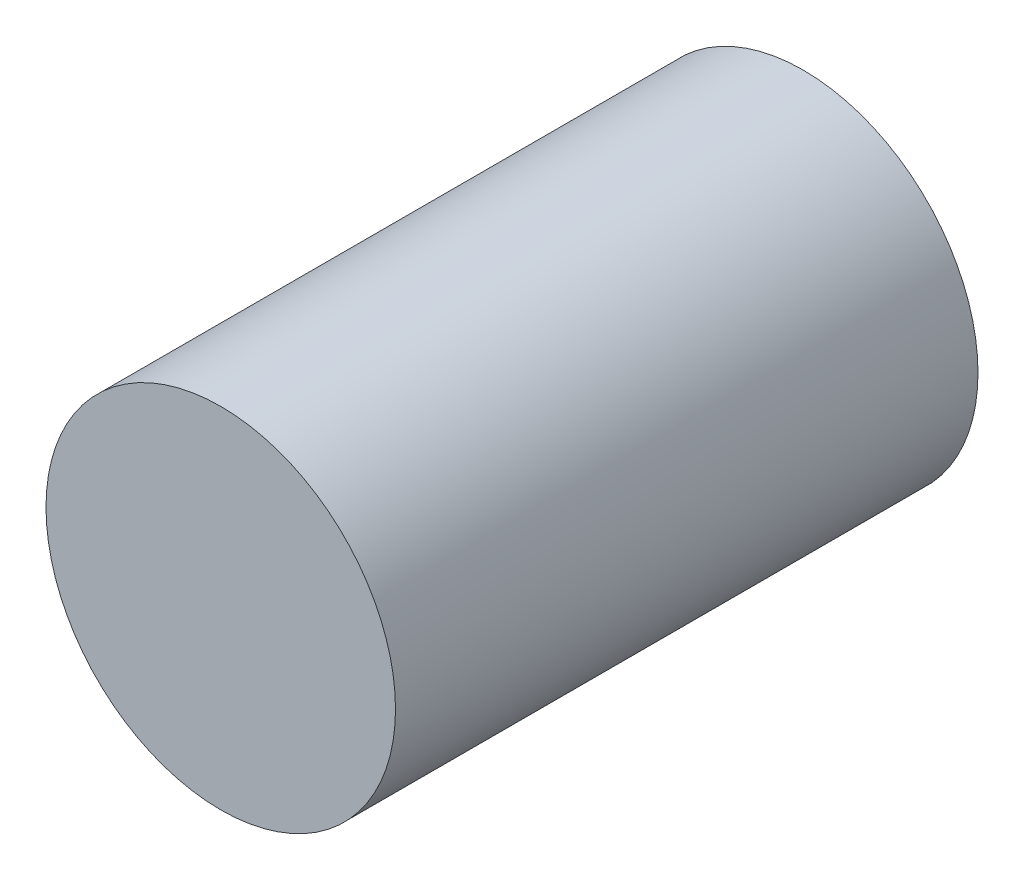
SolidWorks part; units mm, degrees
ref_plane "前视基准面" through (0, 0, 0) normal (0, 0, 1) x (1, 0, 0)
ref_plane "上视基准面" through (0, 0, 0) normal (0, 1, 0) x (1, 0, 0)
ref_plane "右视基准面" through (0, 0, 0) normal (1, 0, 0) x (0, 0, -1)
other "Configuration Table"
sketch "草图1" plane through (0, 0, 0) normal (0, 0, 1) x (1, 0, 0)
  circle A5 centre (0, 0) radius 1.5
  dimension "D1" = 3
extrude "凸台-拉伸1" add sketch "草图1" along normal blind 5
